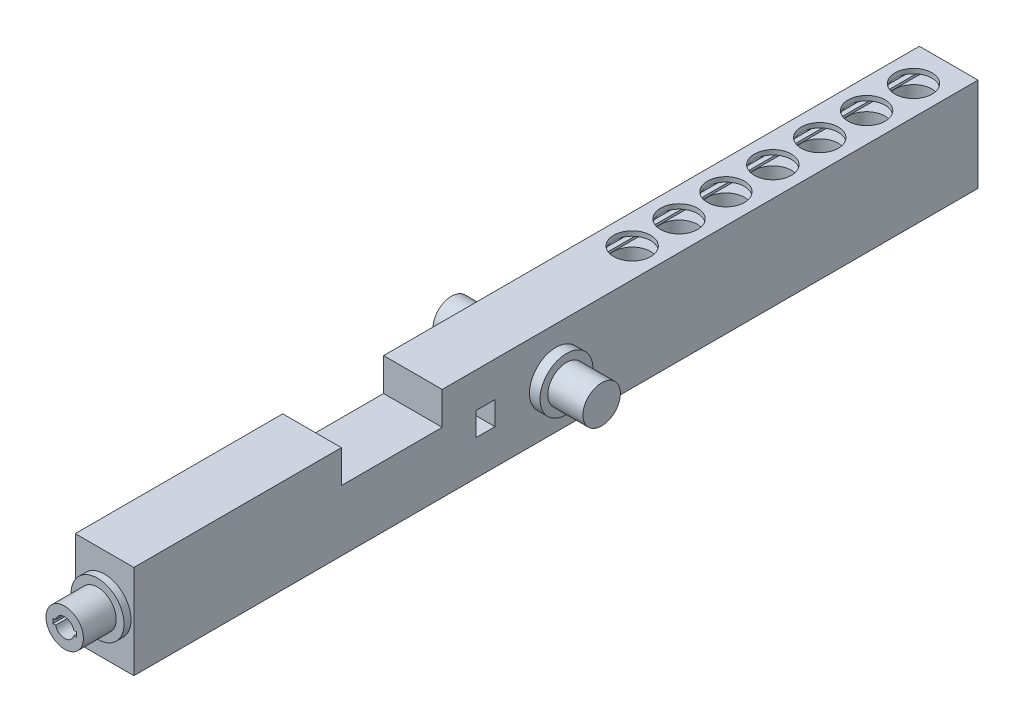
SolidWorks part; units mm, degrees
material "6061 Alloy"
ref_plane "Front Plane" through (0, 0, 0) normal (0, 0, 1) x (1, 0, 0)
ref_plane "Top Plane" through (0, 0, 0) normal (0, 1, 0) x (1, 0, 0)
ref_plane "Right Plane" through (0, 0, 0) normal (1, 0, 0) x (0, 0, -1)
sketch "Sketch1" plane through (0, 0, 0) normal (0, 1, 0) x (1, 0, 0)
  line L1 (-6.25, 90) -> (6.25, 90)
  line L2 (-6.25, 90) -> (-6.25, -90)
  line L3 (-6.25, -90) -> (6.25, -90)
  line L4 (6.25, 90) -> (6.25, -90)
  line L5 (-6.25, 90) -> (6.25, -90) construction
  line L6 (-6.25, -90) -> (6.25, 90) construction
  point P0 (0, 0)
  dimension "D1" = 12.5
  dimension "D2" = 180
extrude "Boss-Extrude1" add sketch "Sketch1" along normal blind 20
sketch "Sketch2" plane through (0, 0, 90) normal (0, 0, 1) x (1, 0, 0)
  line L0 (0, 0) -> (0, 10) construction
  line L1 (-6.25, 0) -> (6.25, 0) construction
  circle A0 centre (0, 10) radius 5.65
  dimension "D2" = 11.3
  dimension "D1" = 10
extrude "Boss-Extrude2" add sketch "Sketch2" along normal blind 1.5
sketch "Sketch3" plane through (0, 0, 91.5) normal (0, 0, 1) x (1, 0, 0)
  line L0 (0, 0) -> (0, 10) construction
  circle A0 centre (0, 10) radius 3.99
  dimension "D1" = 7.98
extrude "Boss-Extrude3" add sketch "Sketch3" along normal blind 7
sketch "Sketch4" plane through (-6.25, 0, 0) normal (-1, 0, 0) x (0, 0, 1)
  line L0 (0, 0) -> (0, 10) construction
  circle A0 centre (0, 10) radius 5.65
  dimension "D2" = 11.3
  dimension "D1" = 10
extrude "Boss-Extrude4" add sketch "Sketch4" along normal blind 2.25
sketch "Sketch5" plane through (-8.5, 0, 0) normal (-1, 0, 0) x (0, 0, 1)
  line L0 (0, 0) -> (0, 10) construction
  line L1 (-90, 0) -> (90, 0) construction
  circle A0 centre (0, 10) radius 3.99
  dimension "D1" = 7.98
extrude "Boss-Extrude5" add sketch "Sketch5" along normal blind 7.5
sketch "Sketch6" plane through (6.25, 0, 0) normal (1, 0, 0) x (0, 0, -1)
  line L0 (0, 0) -> (0, 10) construction
  circle A0 centre (0, 10) radius 5.65
  dimension "D2" = 11.3
  dimension "D1" = 10
extrude "Boss-Extrude6" add sketch "Sketch6" along normal blind 2.25
sketch "Sketch7" plane through (8.5, 0, 0) normal (1, 0, 0) x (0, 0, -1)
  line L0 (0, 0) -> (0, 10) construction
  circle A0 centre (0, 10) radius 3.99
  dimension "D1" = 7.98
extrude "Boss-Extrude7" add sketch "Sketch7" along normal blind 7.5
sketch "Sketch8" plane through (0, 20, 0) normal (0, 1, 0) x (1, 0, 0)
  line L0 (0, 0) -> (0, 90) construction
  line L1 (6.25, 90) -> (-6.25, 90) construction
  circle A0 centre (0, 82.5) radius 3.95
  circle A1 centre (0, 72.5) radius 3.95
  circle A2 centre (0, 62.5) radius 3.95
  circle A3 centre (0, 52.5) radius 3.95
  circle A4 centre (0, 42.5) radius 3.95
  circle A5 centre (0, 32.5) radius 3.95
  circle A6 centre (0, 22.5) radius 3.95
  dimension "D1" = 7.9
  dimension "D2" = 7.9
  dimension "D3" = 7.9
  dimension "D4" = 7.9
  dimension "D5" = 7.9
  dimension "D6" = 7.9
  dimension "D13" = 7.9
  dimension "D7" = 7.5
  dimension "D8" = 10
  dimension "D9" = 10
  dimension "D10" = 10
  dimension "D11" = 10
  dimension "D12" = 10
  dimension "D14" = 10
extrude "Cut-Extrude1" cut sketch "Sketch8" against normal blind 19
sketch "Sketch9" plane through (0, 0, -90) normal (0, 0, -1) x (-1, 0, 0)
  line L0 (0, 0) -> (0, 18) construction
  line L2 (-4, 19) -> (4, 19)
  line L3 (-4, 19) -> (-4, 17)
  line L4 (-4, 17) -> (4, 17)
  line L5 (4, 19) -> (4, 17)
  line L6 (-4, 19) -> (4, 17) construction
  line L7 (-4, 17) -> (4, 19) construction
  dimension "D1" = 18
  dimension "D2" = 8
  dimension "D3" = 2
extrude "Cut-Extrude2" cut sketch "Sketch9" against normal blind 72.5
sketch "Sketch10" plane through (0, 0, -90) normal (0, 0, -1) x (-1, 0, 0)
  line L0 (0, 0) -> (0, 18) construction
  line L1 (-6.25, 0) -> (6.25, 0) construction
  line L3 (-5.75, 18.5) -> (5.75, 18.5)
  line L4 (-5.75, 18.5) -> (-5.75, 17.5)
  line L5 (-5.75, 17.5) -> (5.75, 17.5)
  line L6 (5.75, 18.5) -> (5.75, 17.5)
  line L7 (-5.75, 18.5) -> (5.75, 17.5) construction
  line L8 (-5.75, 17.5) -> (5.75, 18.5) construction
  dimension "D1" = 18
  dimension "D2" = 11.5
  dimension "D3" = 1
extrude "Cut-Extrude3" cut sketch "Sketch10" against normal blind 72.5
sketch "Sketch11" plane through (0, 20, 0) normal (0, 1, 0) x (1, 0, 0)
  line L0 (0, 0) -> (0, -35) construction
  line L1 (6.25, -90) -> (6.25, 90) construction
  line L2 (-6.25, -45.75) -> (6.25, -45.75)
  line L3 (-6.25, -45.75) -> (-6.25, -24.25)
  line L4 (-6.25, -24.25) -> (6.25, -24.25)
  line L5 (6.25, -45.75) -> (6.25, -24.25)
  line L6 (-6.25, -45.75) -> (6.25, -24.25) construction
  line L7 (-6.25, -24.25) -> (6.25, -45.75) construction
  dimension "D1" = 35
  dimension "D2" = 21.5
extrude "Cut-Extrude4" cut sketch "Sketch11" against normal blind 7
sketch "Sketch12" plane through (0, 0, 98.5) normal (0, 0, 1) x (1, 0, 0)
  line L0 (1.9365, 10.5) -> (2.5, 10.5)
  line L1 (-2.5, 9.5) -> (-1.9365, 9.5)
  line L2 (-2.5, 9.5) -> (-2.5, 10.5)
  line L3 (-2.5, 10.5) -> (-1.9365, 10.5)
  line L4 (2.5, 9.5) -> (2.5, 10.5)
  line L5 (-2.5, 9.5) -> (2.5, 10.5) construction
  line L6 (-2.5, 10.5) -> (2.5, 9.5) construction
  line L7 (1.9365, 9.5) -> (2.5, 9.5)
  arc A0 (-1.9365, 9.5) -> (1.9365, 9.5) centre (0, 10) ccw
  arc A1 (1.9365, 10.5) -> (-1.9365, 10.5) centre (0, 10) ccw
  dimension "D1" = 4
  dimension "D2" = 5
  dimension "D3" = 1
extrude "Cut-Extrude5" cut sketch "Sketch12" against normal blind 20
sketch "Sketch14" plane through (6.25, 0, 0) normal (1, 0, 0) x (0, 0, -1)
  line L0 (0, 10) -> (-15, 10) construction
  line L2 (-17, 12.5) -> (-13, 12.5)
  line L3 (-17, 12.5) -> (-17, 7.5)
  line L4 (-17, 7.5) -> (-13, 7.5)
  line L5 (-13, 12.5) -> (-13, 7.5)
  line L6 (-17, 12.5) -> (-13, 7.5) construction
  line L7 (-17, 7.5) -> (-13, 12.5) construction
  dimension "D1" = 15
  dimension "D2" = 5
  dimension "D3" = 4
extrude "Cut-Extrude6" cut sketch "Sketch14" against normal up to surface (12.5 mm away) up to face at (-6.25, 13.25, 17.5)
